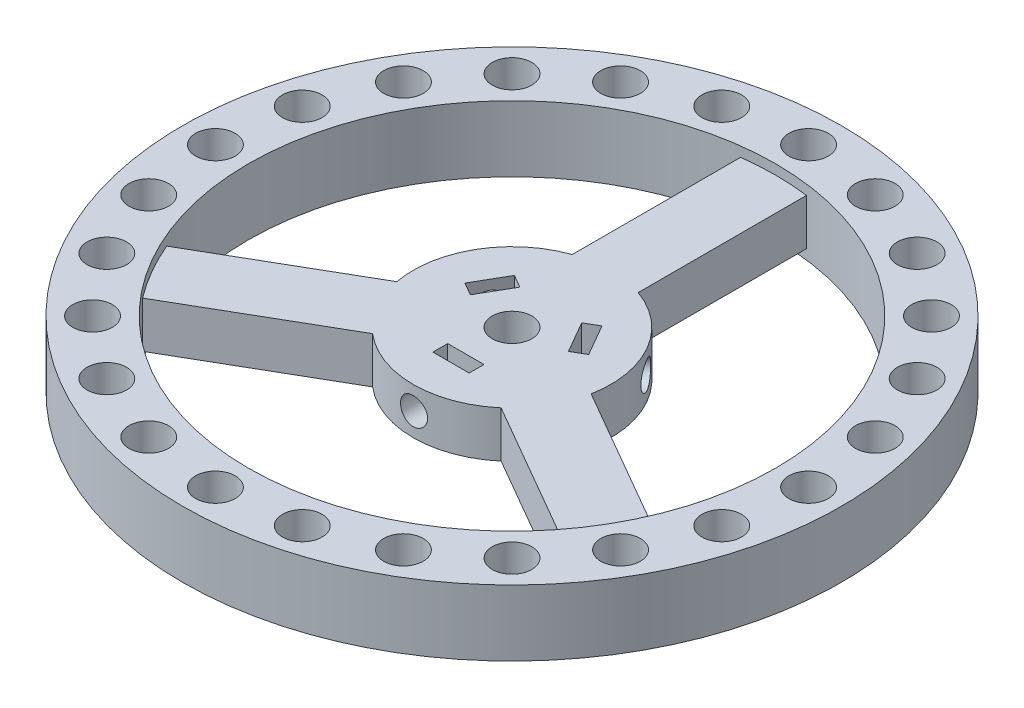
SolidWorks part; units mm, degrees
ref_plane "Front Plane" through (0, 0, 0) normal (0, 0, 1) x (1, 0, 0)
ref_plane "Top Plane" through (0, 0, 0) normal (0, 1, 0) x (1, 0, 0)
ref_plane "Right Plane" through (0, 0, 0) normal (1, 0, 0) x (0, 0, -1)
sketch "Sketch2" plane through (0, 0, 0) normal (0, 1, 0) x (1, 0, 0)
  line L0 (0, -40) -> (0, -50)
  line L1 (0, 0) -> (0, 50)
  line L2 (0, 0) -> (43.3013, -25)
  line L3 (0, 0) -> (-43.3013, -25)
  line L4 (0, 0) -> (10, 0)
  line L5 (5, 0) -> (5, 39.6863)
  line L6 (-5, 0) -> (-5, 39.6863)
  line L7 (8.6603, 43.1835) -> (8.6603, 43.7499)
  line L8 (-8.6603, 43.1835) -> (-8.6603, 43.7499)
  line L9 (-2.5, -4.3301) -> (31.8693, -24.1733)
  line L10 (2.5, 4.3301) -> (36.8693, -15.513)
  line L11 (-2.5, 4.3301) -> (-36.8693, -15.513)
  line L12 (2.5, -4.3301) -> (-31.8693, -24.1733)
  circle A0 centre (0, 0) radius 50
  circle A1 centre (0, 0) radius 40
  circle A3 centre (0, -45) radius 3
  circle A4 centre (-11.6469, -43.4667) radius 3
  circle A5 centre (-22.5, -38.9711) radius 3
  circle A6 centre (-31.8198, -31.8198) radius 3
  circle A7 centre (-38.9711, -22.5) radius 3
  circle A8 centre (-43.4667, -11.6469) radius 3
  circle A9 centre (-45, 0) radius 3
  circle A10 centre (-43.4667, 11.6469) radius 3
  circle A11 centre (-38.9711, 22.5) radius 3
  circle A12 centre (-31.8198, 31.8198) radius 3
  circle A13 centre (-22.5, 38.9711) radius 3
  circle A14 centre (-11.6469, 43.4667) radius 3
  circle A15 centre (0, 45) radius 3
  circle A16 centre (11.6469, 43.4667) radius 3
  circle A17 centre (22.5, 38.9711) radius 3
  circle A18 centre (31.8198, 31.8198) radius 3
  circle A19 centre (38.9711, 22.5) radius 3
  circle A20 centre (43.4667, 11.6469) radius 3
  circle A21 centre (45, 0) radius 3
  circle A22 centre (43.4667, -11.6469) radius 3
  circle A23 centre (38.9711, -22.5) radius 3
  circle A24 centre (31.8198, -31.8198) radius 3
  circle A25 centre (22.5, -38.9711) radius 3
  circle A26 centre (11.6469, -43.4667) radius 3
  circle A29 centre (0, 0) radius 10
  point P15 (0, 0)
  point P62 (0, 25)
  point P80 (0, 0)
  dimension "D1" = 100
  dimension "D2" = 80
  dimension "D4" = 6
  dimension "D7" = 3
  dimension "D8" = 5
  dimension "D3" = 3
  dimension "D6" = 5
  dimension "D9" = 5
  dimension "D5" = 24
extrude "Boss-Extrude4" add sketch "Sketch2" along normal blind 10 contours A7 L3 A0 L0 A3 A1 A6 A5 A4 | A15 L1 A0 L3 A7 A1 A14 A13 A12 A11 A10 A9 A8 | A23 L2 A0 L1 A15 A1 A22 A21 A20 A19 A18 A17 A16 | A23 L2 A1 L0 A3 A0 A26 A25 A24
sketch "Sketch6" plane through (0, 0, 0) normal (0, 1, 0) x (1, 0, 0)
  line L0 (0, 0) -> (0, 40)
  line L1 (0, 0) -> (34.641, -20)
  line L2 (0, 0) -> (-34.641, -20)
  line L3 (-5, 14.1421) -> (-5, 39.6863)
  line L4 (5, 14.1421) -> (5, 39.6863)
  line L5 (9.7474, -11.4012) -> (31.8693, -24.1733)
  line L6 (14.7474, -2.7409) -> (36.8693, -15.513)
  line L7 (-14.7474, -2.7409) -> (-36.8693, -15.513)
  line L8 (-9.7474, -11.4012) -> (-31.8693, -24.1733)
  circle A0 centre (0, 0) radius 15
  circle A1 centre (0, 0) radius 40 construction
  circle A2 centre (0, 0) radius 40
  point P12 (0, 0)
  point P24 (0, 0)
  dimension "D1" = 30
  dimension "D3" = 5
  dimension "D5" = 5
  dimension "D6" = 5
  dimension "D2" = 3
  dimension "D4" = 3
extrude "Boss-Extrude8" add sketch "Sketch6" along normal blind 3.5 and the other way blind 3.5 from offset 5 contours L7 A2 L2 A0 | L2 A2 L8 A0 | L0 A0 L2 | L1 A0 L0 | A0 L1 L2 | L4 A2 L0 A0 | L0 A2 L3 A0 | L1 A2 L6 A0 | L5 A2 L1 A0
sketch "Sketch7" plane through (0, 8.5, 0) normal (0, 1, 0) x (1, 0, 0)
  line L0 (0, -3.005) -> (0, -7.005)
  line L1 (-2.75, -7.005) -> (2.75, -7.005)
  line L2 (-4.6915, 5.8841) -> (-7.4415, 1.1209)
  line L3 (-2.75, -7.005) -> (2.75, -7.005)
  line L4 (-2.75, -7.005) -> (-2.75, -9.255)
  line L5 (-2.75, -9.255) -> (2.75, -9.255)
  line L6 (2.75, -7.005) -> (2.75, -9.255)
  line L11 (-4.6915, 5.8841) -> (-6.6401, 7.0091)
  line L16 (-7.4415, 1.1209) -> (-9.3901, 2.2459)
  line L17 (-6.6401, 7.0091) -> (-9.3901, 2.2459)
  line L18 (7.4415, 1.1209) -> (4.6915, 5.8841)
  line L19 (7.4415, 1.1209) -> (9.3901, 2.2459)
  line L20 (4.6915, 5.8841) -> (6.6401, 7.0091)
  line L21 (9.3901, 2.2459) -> (6.6401, 7.0091)
  line L22 (0, 0) -> (0, -3.005)
  line L23 (0, 0) -> (-6.0665, 3.5025)
  line L24 (0, 0) -> (6.0665, 3.5025)
  circle A0 centre (0, 0) radius 3.005
  point P8 (0, -7.005)
  point P21 (0, 0)
  point P24 (0, 0)
  dimension "D1" = 6.01
  dimension "D2" = 4
  dimension "D3" = 2.75
  dimension "D4" = 2.25
extrude "Cut-Extrude2" cut sketch "Sketch7" against normal through all contours L11 L17 L16 L2 | L24 A0 L23 | L23 A0 L22 | L22 A0 L24 | L19 L21 L20 L18 | L6 L1 L4 L5
sketch "Sketch11" plane through (6.0665, 0, -3.5025) normal (0.866, 0, -0.5) x (-0.5, 0, -0.866)
  line L0 (0, 0) -> (0, 10)
  line L1 (3, 10) -> (-3, 10) construction
  circle A0 centre (0, 5) radius 2.05
sketch "Sketch12" plane through (0, 0, 7.005) normal (0, 0, 1) x (1, 0, 0)
  line L0 (0, 0) -> (0, 10)
  line L1 (-50, 0) -> (50, 0) construction
  line L2 (50, 10) -> (-50, 10) construction
  circle A0 centre (0, 5) radius 2.05
sketch "Sketch13" plane through (-6.0665, 0, -3.5025) normal (-0.866, 0, -0.5) x (-0.5, 0, 0.866)
  line L0 (0, 0) -> (0, 10)
  line L1 (-50, 0) -> (50, 0) construction
  line L2 (3, 10) -> (-3, 10) construction
  circle A0 centre (0, 5) radius 2.05
extrude "Cut-Extrude3" cut sketch "Sketch13" along normal blind 16 contours L0 A0 | L0 A0
extrude "Cut-Extrude4" cut sketch "Sketch12" along normal blind 17 contours L0 A0 | L0 A0
extrude "Cut-Extrude5" cut sketch "Sketch11" along normal blind 22 contours L0 A0 | L0 A0
